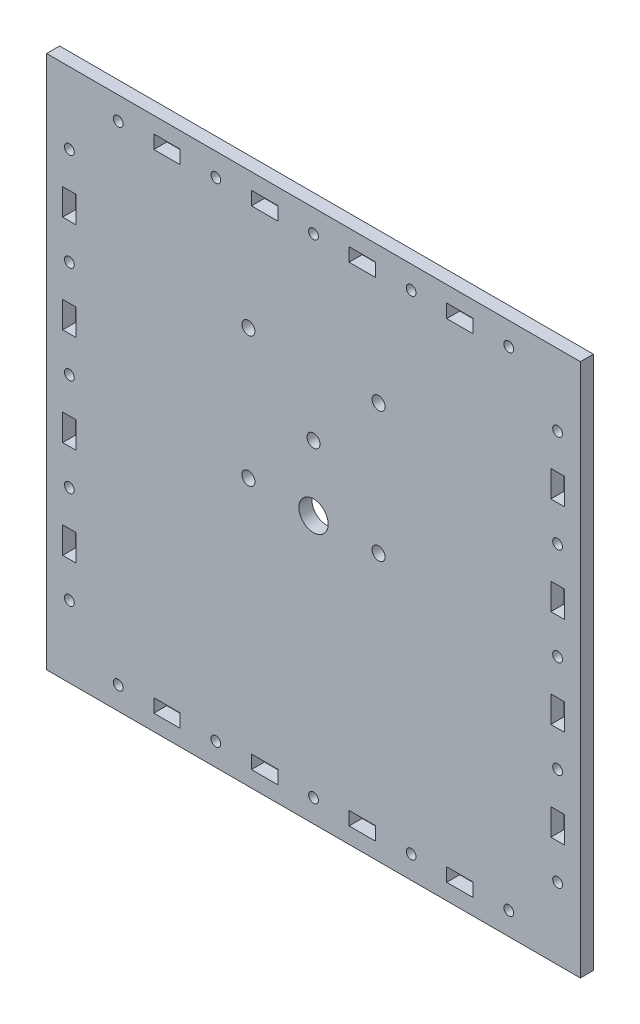
SolidWorks part; units mm, degrees
ref_plane "前视基准面" through (0, 0, 0) normal (0, 0, 1) x (1, 0, 0)
ref_plane "上视基准面" through (0, 0, 0) normal (0, 1, 0) x (1, 0, 0)
ref_plane "右视基准面" through (0, 0, 0) normal (1, 0, 0) x (0, 0, -1)
sketch "草图1" plane through (0, 0, 0) normal (0, 0, 1) x (1, 0, 0)
  line L261 (47.0274, 35.0547) -> (47.0274, 15.0547) construction
  line L315 (47.0274, 15.0547) -> (27.0274, 15.0547) construction
  line L316 (-12.9726, 90.0547) -> (2.0274, 90.0547) construction
  line L332 (-2.0326, 92.1192) -> (6.0874, 87.9902) construction
  line L334 (57.9674, 92.1192) -> (66.0874, 92.1192)
  line L335 (57.9674, 92.1192) -> (57.9674, 87.9902)
  line L336 (57.9674, 87.9902) -> (66.0874, 87.9902)
  line L337 (66.0874, 92.1192) -> (66.0874, 87.9902)
  line L338 (57.9674, 92.1192) -> (66.0874, 87.9902) construction
  line L339 (57.9674, 87.9902) -> (66.0874, 92.1192) construction
  line L389 (62.0274, 90.0547) -> (62.0274, 92.1192) construction
  line L390 (77.0274, 90.0547) -> (77.0274, 99.5851) construction
  line L395 (62.0274, 90.0547) -> (92.0274, 90.0547) construction
  line L418 (92.0274, 90.0547) -> (92.0274, 92.1192) construction
  line L419 (96.0874, 87.9902) -> (87.9674, 92.1192) construction
  line L420 (96.0874, 92.1192) -> (87.9674, 87.9902) construction
  line L421 (107.0274, 90.0547) -> (92.0274, 90.0547) construction
  line L422 (87.9674, 92.1192) -> (87.9674, 87.9902)
  line L423 (96.0874, 87.9902) -> (87.9674, 87.9902)
  line L424 (96.0874, 92.1192) -> (96.0874, 87.9902)
  line L443 (96.0874, 92.1192) -> (87.9674, 92.1192)
  line L444 (-2.0326, 87.9902) -> (6.0874, 92.1192) construction
  line L445 (2.0274, 90.0547) -> (2.0274, 92.1192) construction
  line L446 (32.0274, 90.0547) -> (2.0274, 90.0547) construction
  line L447 (17.0274, 90.0547) -> (17.0274, 99.5851) construction
  line L448 (32.0274, 90.0547) -> (32.0274, 92.1192) construction
  line L449 (36.0874, 87.9902) -> (27.9674, 92.1192) construction
  line L483 (36.0874, 92.1192) -> (27.9674, 87.9902) construction
  line L484 (-2.0326, 92.1192) -> (6.0874, 92.1192)
  line L485 (-2.0326, 92.1192) -> (-2.0326, 87.9902)
  line L486 (-2.0326, 87.9902) -> (6.0874, 87.9902)
  line L487 (6.0874, 92.1192) -> (6.0874, 87.9902)
  line L488 (27.9674, 92.1192) -> (27.9674, 87.9902)
  line L489 (36.0874, 87.9902) -> (27.9674, 87.9902)
  line L490 (36.0874, 92.1192) -> (36.0874, 87.9902)
  line L491 (36.0874, 92.1192) -> (27.9674, 92.1192)
  line L492 (124.0919, 4.1147) -> (124.0919, -4.0053)
  line L493 (124.0919, 4.1147) -> (119.9629, 4.1147)
  line L494 (119.9629, 4.1147) -> (119.9629, -4.0053)
  line L495 (124.0919, -4.0053) -> (119.9629, -4.0053)
  line L496 (124.0919, -25.8853) -> (119.9629, -25.8853)
  line L497 (119.9629, -34.0053) -> (119.9629, -25.8853)
  line L498 (124.0919, -34.0053) -> (119.9629, -34.0053)
  line L499 (124.0919, -34.0053) -> (124.0919, -25.8853)
  line L500 (124.0919, 64.1147) -> (124.0919, 55.9947)
  line L501 (124.0919, 64.1147) -> (119.9629, 64.1147)
  line L502 (119.9629, 64.1147) -> (119.9629, 55.9947)
  line L503 (124.0919, 55.9947) -> (119.9629, 55.9947)
  line L504 (124.0919, 34.1147) -> (119.9629, 34.1147)
  line L505 (119.9629, 25.9947) -> (119.9629, 34.1147)
  line L506 (124.0919, 25.9947) -> (119.9629, 25.9947)
  line L507 (124.0919, 25.9947) -> (124.0919, 34.1147)
  line L508 (122.0274, 75.0547) -> (122.0274, 60.0547) construction
  line L509 (124.0919, 64.1147) -> (119.9629, 55.9947) construction
  line L510 (124.0919, 4.1147) -> (119.9629, -4.0053) construction
  line L511 (119.9629, 4.1147) -> (124.0919, -4.0053) construction
  line L512 (122.0274, 0.0547) -> (124.0919, 0.0547) construction
  line L513 (122.0274, -14.9453) -> (131.5578, -14.9453) construction
  line L514 (122.0274, 0.0547) -> (122.0274, -29.9453) construction
  line L515 (122.0274, -29.9453) -> (124.0919, -29.9453) construction
  line L516 (119.9629, -34.0053) -> (124.0919, -25.8853) construction
  line L517 (124.0919, -34.0053) -> (119.9629, -25.8853) construction
  line L518 (122.0274, -44.9453) -> (122.0274, -29.9453) construction
  line L519 (119.9629, 64.1147) -> (124.0919, 55.9947) construction
  line L520 (122.0274, 60.0547) -> (124.0919, 60.0547) construction
  line L521 (122.0274, 30.0547) -> (122.0274, 60.0547) construction
  line L522 (122.0274, 45.0547) -> (131.5578, 45.0547) construction
  line L523 (122.0274, 30.0547) -> (124.0919, 30.0547) construction
  line L524 (119.9629, 25.9947) -> (124.0919, 34.1147) construction
  line L525 (124.0919, 25.9947) -> (119.9629, 34.1147) construction
  line L526 (36.0874, -62.0098) -> (27.9674, -62.0098)
  line L527 (36.0874, -62.0098) -> (36.0874, -57.8808)
  line L528 (36.0874, -57.8808) -> (27.9674, -57.8808)
  line L529 (27.9674, -62.0098) -> (27.9674, -57.8808)
  line L530 (6.0874, -62.0098) -> (6.0874, -57.8808)
  line L531 (-2.0326, -57.8808) -> (6.0874, -57.8808)
  line L532 (-2.0326, -62.0098) -> (-2.0326, -57.8808)
  line L533 (-2.0326, -62.0098) -> (6.0874, -62.0098)
  line L534 (96.0874, -62.0098) -> (87.9674, -62.0098)
  line L535 (96.0874, -62.0098) -> (96.0874, -57.8808)
  line L536 (96.0874, -57.8808) -> (87.9674, -57.8808)
  line L537 (87.9674, -62.0098) -> (87.9674, -57.8808)
  line L538 (66.0874, -62.0098) -> (66.0874, -57.8808)
  line L539 (57.9674, -57.8808) -> (66.0874, -57.8808)
  line L540 (57.9674, -62.0098) -> (57.9674, -57.8808)
  line L541 (57.9674, -62.0098) -> (66.0874, -62.0098)
  line L542 (107.0274, -59.9453) -> (92.0274, -59.9453) construction
  line L543 (96.0874, -62.0098) -> (87.9674, -57.8808) construction
  line L544 (36.0874, -62.0098) -> (27.9674, -57.8808) construction
  line L545 (36.0874, -57.8808) -> (27.9674, -62.0098) construction
  line L546 (32.0274, -59.9453) -> (32.0274, -62.0098) construction
  line L547 (17.0274, -59.9453) -> (17.0274, -69.4756) construction
  line L548 (32.0274, -59.9453) -> (2.0274, -59.9453) construction
  line L549 (2.0274, -59.9453) -> (2.0274, -62.0098) construction
  line L550 (-2.0326, -57.8808) -> (6.0874, -62.0098) construction
  line L551 (-2.0326, -62.0098) -> (6.0874, -57.8808) construction
  line L552 (-12.9726, -59.9453) -> (2.0274, -59.9453) construction
  line L553 (96.0874, -57.8808) -> (87.9674, -62.0098) construction
  line L554 (92.0274, -59.9453) -> (92.0274, -62.0098) construction
  line L555 (62.0274, -59.9453) -> (92.0274, -59.9453) construction
  line L556 (77.0274, -59.9453) -> (77.0274, -69.4756) construction
  line L557 (62.0274, -59.9453) -> (62.0274, -62.0098) construction
  line L558 (57.9674, -57.8808) -> (66.0874, -62.0098) construction
  line L559 (57.9674, -62.0098) -> (66.0874, -57.8808) construction
  line L560 (-30.0371, 25.9947) -> (-30.0371, 34.1147)
  line L561 (-30.0371, 25.9947) -> (-25.9081, 25.9947)
  line L562 (-25.9081, 25.9947) -> (-25.9081, 34.1147)
  line L563 (-30.0371, 34.1147) -> (-25.9081, 34.1147)
  line L564 (-30.0371, 55.9947) -> (-25.9081, 55.9947)
  line L565 (-25.9081, 64.1147) -> (-25.9081, 55.9947)
  line L566 (-30.0371, 64.1147) -> (-25.9081, 64.1147)
  line L567 (-30.0371, 64.1147) -> (-30.0371, 55.9947)
  line L568 (-30.0371, -34.0053) -> (-30.0371, -25.8853)
  line L569 (-30.0371, -34.0053) -> (-25.9081, -34.0053)
  line L570 (-25.9081, -34.0053) -> (-25.9081, -25.8853)
  line L571 (-30.0371, -25.8853) -> (-25.9081, -25.8853)
  line L572 (-30.0371, -4.0053) -> (-25.9081, -4.0053)
  line L573 (-25.9081, 4.1147) -> (-25.9081, -4.0053)
  line L574 (-30.0371, 4.1147) -> (-25.9081, 4.1147)
  line L575 (-30.0371, 4.1147) -> (-30.0371, -4.0053)
  line L576 (-27.9726, -44.9453) -> (-27.9726, -29.9453) construction
  line L577 (-30.0371, -34.0053) -> (-25.9081, -25.8853) construction
  line L578 (-30.0371, 25.9947) -> (-25.9081, 34.1147) construction
  line L579 (-25.9081, 25.9947) -> (-30.0371, 34.1147) construction
  line L580 (-27.9726, 30.0547) -> (-30.0371, 30.0547) construction
  line L581 (-27.9726, 45.0547) -> (-37.5029, 45.0547) construction
  line L582 (-27.9726, 30.0547) -> (-27.9726, 60.0547) construction
  line L583 (-27.9726, 60.0547) -> (-30.0371, 60.0547) construction
  line L584 (-25.9081, 64.1147) -> (-30.0371, 55.9947) construction
  line L585 (-30.0371, 64.1147) -> (-25.9081, 55.9947) construction
  line L586 (-27.9726, 75.0547) -> (-27.9726, 60.0547) construction
  line L587 (-25.9081, -34.0053) -> (-30.0371, -25.8853) construction
  line L588 (-27.9726, -29.9453) -> (-30.0371, -29.9453) construction
  line L589 (-27.9726, 0.0547) -> (-27.9726, -29.9453) construction
  line L590 (-27.9726, -14.9453) -> (-37.5029, -14.9453) construction
  line L591 (-27.9726, 0.0547) -> (-30.0371, 0.0547) construction
  line L592 (-25.9081, 4.1147) -> (-30.0371, -4.0053) construction
  line L593 (-30.0371, 4.1147) -> (-25.9081, -4.0053) construction
  line L594 (47.0274, 15.0547) -> (67.0274, 15.0547) construction
  line L595 (129.0274, 97.0547) -> (-34.9726, 97.0547)
  line L596 (129.0274, 97.0547) -> (129.0274, -66.9453)
  line L597 (129.0274, -66.9453) -> (-34.9726, -66.9453)
  line L598 (-34.9726, 97.0547) -> (-34.9726, -66.9453)
  line L599 (67.0274, 15.0547) -> (67.0274, 55.0547) construction
  line L600 (67.0274, 55.0547) -> (27.0274, 55.0547) construction
  circle A39 centre (47.0274, 90.0547) radius 1.5
  circle A42 centre (47.0274, 15.0547) radius 4.5
  circle A49 centre (77.0274, 90.0547) radius 1.5
  circle A69 centre (107.0274, 90.0547) radius 1.5
  circle A70 centre (-12.9726, 90.0547) radius 1.5
  circle A71 centre (67.0274, 15.0547) radius 2
  circle A72 centre (17.0274, 90.0547) radius 1.5
  circle A73 centre (122.0274, 15.0547) radius 1.5
  circle A74 centre (122.0274, -14.9453) radius 1.5
  circle A75 centre (122.0274, -44.9453) radius 1.5
  circle A76 centre (122.0274, 75.0547) radius 1.5
  circle A77 centre (67.0274, 55.0547) radius 2
  circle A78 centre (122.0274, 45.0547) radius 1.5
  circle A79 centre (47.0274, -59.9453) radius 1.5
  circle A80 centre (17.0274, -59.9453) radius 1.5
  circle A81 centre (-12.9726, -59.9453) radius 1.5
  circle A82 centre (107.0274, -59.9453) radius 1.5
  circle A83 centre (77.0274, -59.9453) radius 1.5
  circle A84 centre (-27.9726, 15.0547) radius 1.5
  circle A85 centre (-27.9726, 45.0547) radius 1.5
  circle A86 centre (-27.9726, 75.0547) radius 1.5
  circle A87 centre (-27.9726, -44.9453) radius 1.5
  circle A88 centre (-27.9726, -14.9453) radius 1.5
  circle A89 centre (27.0274, 55.0547) radius 2
  circle A90 centre (27.0274, 15.0547) radius 2
  circle A91 centre (47.0274, 35.0547) radius 2
  point P5 (210.9534, 218.4629)
  point P6 (288.6284, 218.4629)
  dimension "D1" = 15
  dimension "D3" = 82
  dimension "D5" = 82
  dimension "D4" = 82
  dimension "D6" = 82
  dimension "D2" = 75
extrude "凸台-拉伸1" add sketch "草图1" along normal blind 4
